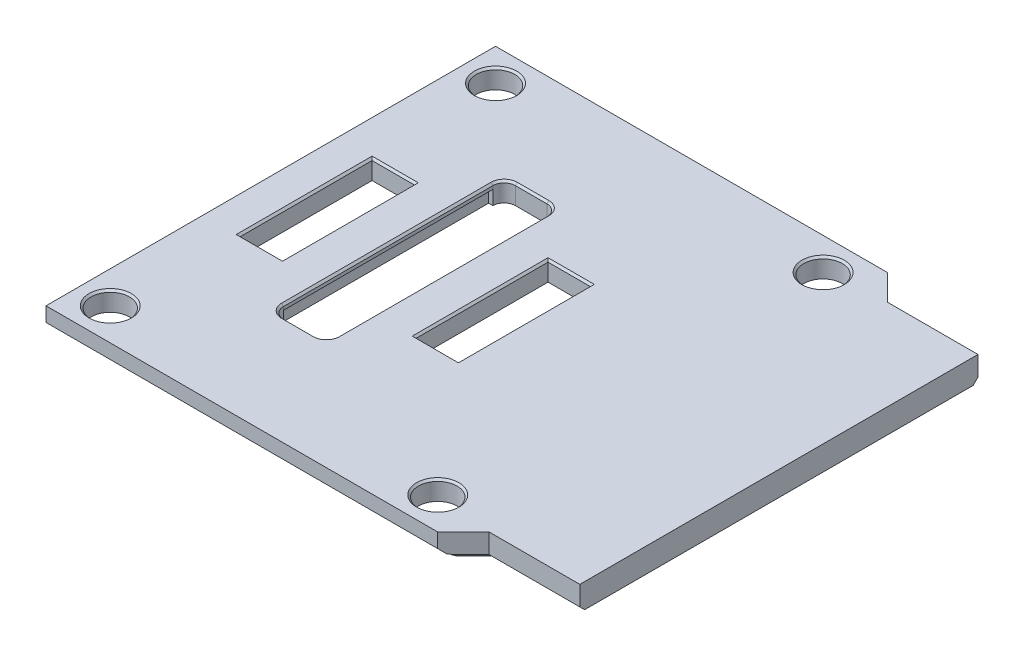
SolidWorks part; units mm, degrees
ref_plane "Front Plane" through (0, 0, 0) normal (0, 0, 1) x (1, 0, 0)
ref_plane "Top Plane" through (0, 0, 0) normal (0, 1, 0) x (1, 0, 0)
ref_plane "Right Plane" through (0, 0, 0) normal (1, 0, 0) x (0, 0, -1)
sketch "Sketch3" plane through (0, 0, 0) normal (0, 1, 0) x (1, 0, 0)
  line L0 (13.7, 0) -> (0, 0) construction
  line L1 (16.75, 10.025) -> (10.65, 10.025)
  line L2 (16.75, 10.025) -> (16.75, -10.025)
  line L3 (16.75, -10.025) -> (10.65, -10.025)
  line L4 (3.96, -16.3) -> (3.96, 16.3)
  line L5 (-2.46, -17.8) -> (2.46, -17.8)
  line L6 (-3.96, 16.3) -> (-3.96, -16.3)
  line L7 (2.46, 17.8) -> (-2.46, 17.8)
  line L8 (0, 17.8) -> (0, -17.8) construction
  line L9 (10.65, 10.025) -> (10.65, -10.025)
  line L10 (16.75, 10.025) -> (10.65, -10.025) construction
  line L11 (16.75, -10.025) -> (10.65, 10.025) construction
  line L12 (-16.75, -10.025) -> (-10.65, -10.025)
  line L13 (-16.75, 10.025) -> (-16.75, -10.025)
  line L14 (-16.75, 10.025) -> (-10.65, 10.025)
  line L15 (-10.65, 10.025) -> (-10.65, -10.025)
  arc A0 (-2.46, 17.8) -> (-3.96, 16.3) centre (-2.46, 16.3) ccw
  arc A1 (3.96, 16.3) -> (2.46, 17.8) centre (2.46, 16.3) ccw
  arc A2 (2.46, -17.8) -> (3.96, -16.3) centre (2.46, -16.3) ccw
  arc A3 (-3.96, -16.3) -> (-2.46, -17.8) centre (-2.46, -16.3) ccw
  point P9 (0, 0)
  point P23 (0, 0)
  dimension "D2" = 1.5
  dimension "D1" = 13.7
  dimension "D3" = 7.92
  dimension "D4" = 20.05
  dimension "D5" = 6.1
  dimension "D6" = 35.6
sketch "Sketch21" plane through (0, 0, 0) normal (0, 1, 0) x (1, 0, 0)
  line L1 (38.5, 35) -> (-22.5, 35)
  line L7 (38.5, 35) -> (42.5, 31)
  line L8 (-22.5, 35) -> (-22.5, -35)
  line L9 (-22.5, 0) -> (0, 0) construction
  line L10 (0, 0) -> (38.5, 0) construction
  line L11 (38.5, -35) -> (38.5, 35) construction
  line L12 (38.5, -35) -> (-22.5, -35)
  line L13 (42.5, 31) -> (56.625, 31)
  line L14 (56.625, 31) -> (56.625, -31)
  line L15 (56.625, 0) -> (38.5, 0) construction
  line L16 (42.5, -31) -> (56.625, -31)
  line L17 (38.5, -35) -> (42.5, -31)
  line L26 (16.75, 10.025) -> (10.65, 10.025)
  line L27 (10.65, 10.025) -> (10.65, -10.025)
  line L28 (10.65, -10.025) -> (16.75, -10.025)
  line L29 (16.75, -10.025) -> (16.75, 10.025)
  line L30 (16.75, 10.025) -> (10.65, 10.025) construction
  line L31 (10.65, 10.025) -> (10.65, -10.025) construction
  line L32 (10.65, -10.025) -> (16.75, -10.025) construction
  line L33 (16.75, -10.025) -> (16.75, 10.025) construction
  line L34 (-10.4, -10.275) -> (-10.4, 10.275)
  line L35 (-10.4, 10.275) -> (-17, 10.275)
  line L36 (-17, 10.275) -> (-17, -10.275)
  line L37 (-17, -10.275) -> (-10.4, -10.275)
  line L38 (-16.75, -10.025) -> (-10.65, -10.025)
  line L39 (-10.65, -10.025) -> (-10.65, 10.025)
  line L40 (-10.65, 10.025) -> (-16.75, 10.025)
  line L41 (-16.75, 10.025) -> (-16.75, -10.025)
  line L42 (-16.75, -10.025) -> (-10.65, -10.025) construction
  line L43 (-10.65, -10.025) -> (-10.65, 10.025) construction
  line L44 (-10.65, 10.025) -> (-16.75, 10.025) construction
  line L45 (-16.75, 10.025) -> (-16.75, -10.025) construction
  line L46 (-3.96, 16.3) -> (-3.96, -16.3)
  line L47 (2.46, 17.8) -> (-2.46, 17.8)
  line L48 (3.96, -16.3) -> (3.96, 16.3)
  line L49 (-2.46, -17.8) -> (2.46, -17.8)
  line L50 (-3.96, 16.3) -> (-3.96, -16.3) construction
  line L51 (2.46, 17.8) -> (-2.46, 17.8) construction
  line L52 (3.96, -16.3) -> (3.96, 16.3) construction
  line L53 (-2.46, -17.8) -> (2.46, -17.8) construction
  line L54 (-4.21, 16.3) -> (-4.21, -16.3)
  line L55 (-2.46, -18.05) -> (2.46, -18.05)
  line L56 (4.21, -16.3) -> (4.21, 16.3)
  line L57 (2.46, 18.05) -> (-2.46, 18.05)
  line L58 (17, 10.275) -> (10.4, 10.275)
  line L59 (10.4, 10.275) -> (10.4, -10.275)
  line L60 (10.4, -10.275) -> (17, -10.275)
  line L61 (17, -10.275) -> (17, 10.275)
  circle A4 centre (-17.5, 30) radius 1.6 construction
  circle A5 centre (33.5, 30) radius 1.6 construction
  circle A6 centre (33.5, -30) radius 1.6 construction
  circle A7 centre (-17.5, -30) radius 1.6 construction
  circle A8 centre (-17.5, 30) radius 3
  circle A9 centre (-17.5, -30) radius 3
  circle A10 centre (33.5, -30) radius 3
  circle A11 centre (33.5, 30) radius 3
  arc A12 (-4.21, -16.3) -> (-2.46, -18.05) centre (-2.46, -16.3) ccw
  arc A13 (2.46, -18.05) -> (4.21, -16.3) centre (2.46, -16.3) ccw
  arc A14 (4.21, 16.3) -> (2.46, 18.05) centre (2.46, 16.3) ccw
  arc A15 (-2.46, 18.05) -> (-4.21, 16.3) centre (-2.46, 16.3) ccw
  arc A16 (-2.46, 17.8) -> (-3.96, 16.3) centre (-2.46, 16.3) ccw
  arc A17 (3.96, 16.3) -> (2.46, 17.8) centre (2.46, 16.3) ccw
  arc A18 (2.46, -17.8) -> (3.96, -16.3) centre (2.46, -16.3) ccw
  arc A19 (-3.96, -16.3) -> (-2.46, -17.8) centre (-2.46, -16.3) ccw
  arc A20 (-2.46, 17.8) -> (-3.96, 16.3) centre (-2.46, 16.3) ccw construction
  arc A21 (3.96, 16.3) -> (2.46, 17.8) centre (2.46, 16.3) ccw construction
  arc A22 (2.46, -17.8) -> (3.96, -16.3) centre (2.46, -16.3) ccw construction
  arc A23 (-3.96, -16.3) -> (-2.46, -17.8) centre (-2.46, -16.3) ccw construction
  dimension "D16" = 3.2
  dimension "D2" = 6
  dimension "D3" = 0
  dimension "D4" = 0
  dimension "D5" = 0
  dimension "D6" = 0.25
  dimension "D9" = 22.5
  dimension "D10" = 61
  dimension "D11" = 35
  dimension "D12" = 5
  dimension "D13" = 5
  dimension "D14" = 5
  dimension "D15" = 5
  dimension "D17" = 45
  dimension "D18" = 4
  dimension "D19" = 14.125
extrude "Boss-Extrude3" add sketch "Sketch21" along normal blind 3
sketch "Sketch28" plane through (0, 0, 0) normal (0, -1, 0) x (1, 0, 0)
  line L9 (42.5, -31) -> (56.625, -31) construction
  line L13 (39.5, 34) -> (39.5, -34)
  line L14 (38.5, 35) -> (39.5, 34) construction
  line L17 (56.625, -31) -> (56.625, 31) construction
  line L18 (42.5, 31) -> (56.625, 31) construction
  line L19 (38.5, 35) -> (38.5, -35) construction
  line L20 (42.5, -31) -> (56.625, -31)
  line L21 (56.625, -31) -> (56.625, 31)
  line L22 (42.5, 31) -> (56.625, 31)
  line L23 (38.5, 35) -> (38.5, -35) construction
  line L24 (38.5, -35) -> (42.5, -31) construction
  line L25 (39.5, -34) -> (42.5, -31)
  line L26 (38.5, 35) -> (42.5, 31) construction
  line L27 (39.5, 34) -> (42.5, 31)
  line L28 (38.5, -35) -> (39.5, -34) construction
  dimension "D1" = 1
extrude "Boss-Extrude2" add sketch "Sketch28" along normal blind 0.8
sketch "Sketch29" plane through (0, 0, 0) normal (0, -1, 0) x (1, 0, 0)
  line L0 (-4.21, 16.3) -> (-4.875, 16.3)
  line L1 (-4.875, 16.3) -> (-4.875, -16.3)
  line L2 (-4.875, -16.3) -> (-4.21, -16.3)
  line L3 (-4.21, -16.3) -> (4.21, -16.3)
  line L4 (4.21, -16.3) -> (4.875, -16.3)
  line L5 (4.875, -16.3) -> (4.875, 16.3)
  line L6 (4.875, 16.3) -> (4.21, 16.3)
  line L7 (4.21, 16.3) -> (-4.21, 16.3)
  line L8 (0, 16.3) -> (0, 0) construction
  line L9 (0, 0) -> (4.875, 0) construction
  line L10 (0, 0) -> (-4.875, 0) construction
  arc A0 (-4.21, -16.3) -> (-2.46, -18.05) centre (-2.46, -16.3) ccw construction
  dimension "D1" = 9.75
extrude "Cut-Extrude1" cut sketch "Sketch29" against normal blind 2.2
sketch "Sketch30" plane through (0, 0, 0) normal (0, -1, 0) x (1, 0, 0)
  line L0 (30, -14.5) -> (30, 35) construction
  line L2 (-22.5, 35) -> (38.5, 35) construction
  text T0 "Ms5p" font "Microsoft Sans Serif" height 8
  dimension "D1" = 30
  dimension "D2" = 14.5
extrude "Cut-Extrude2" cut sketch "Sketch30" against normal blind 1
chamfer "Chamfer1" distance 0.3 angle 45 20 edges at (33.5, 3, 33) (-17.5, 3, 33) (-17.5, 3, -27) (33.5, 3, -27) (17, 3, 0) (13.7, 3, -10.275) (10.4, 3, 0) (13.7, 3, 10.275) (-13.7, 3, 10.275) (-17, 3, 0) (-10.4, 3, 0) (-13.7, 3, -10.275) (0, 3, 18.05) (3.6974, 3, 17.5374) (-3.6974, 3, 17.5374) (4.21, 3, 0) (-4.21, 3, 0) (3.6974, 3, -17.5374) (-3.6974, 3, -17.5374) (0, 3, -18.05)
chamfer "Chamfer2" distance 0.75 angle 45 8 edges at (41, -0.8, -32.5) (49.5625, -0.8, -31) (56.625, -0.8, 0) (49.5625, -0.8, 31) (41, -0.8, 32.5) (8, 0, -35) (8, 0, 35) (-22.5, 0, 0)
